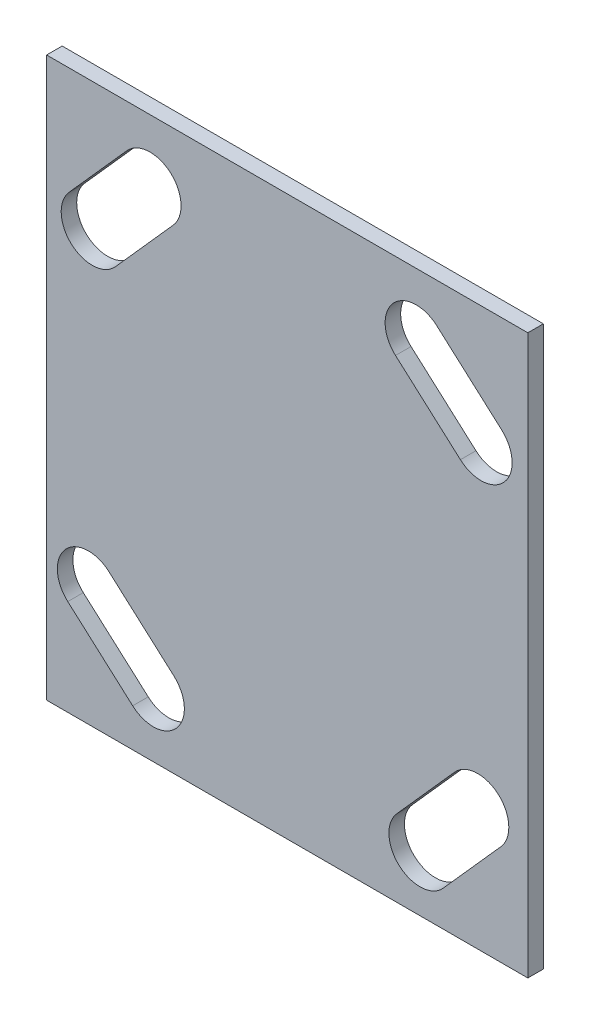
SolidWorks part; units mm, degrees
ref_plane "Front Plane" through (0, 0, 0) normal (0, 0, 1) x (1, 0, 0)
ref_plane "Top Plane" through (0, 0, 0) normal (0, 1, 0) x (1, 0, 0)
ref_plane "Right Plane" through (0, 0, 0) normal (1, 0, 0) x (0, 0, -1)
sketch "Flat Plate" plane through (0, 0, 0) normal (0, 0, 1) x (1, 0, 0)
  line L1 (-101.3811, 38.1949) -> (-2.9561, 38.1949)
  line L2 (-101.3811, 38.1949) -> (-101.3811, -76.1051)
  line L3 (-101.3811, -76.1051) -> (-2.9561, -76.1051)
  line L4 (-2.9561, 38.1949) -> (-2.9561, -76.1051)
  point P4 (-234.7829, 69.0702)
  dimension "D1" = 98.425
  dimension "D2" = 114.3
extrude "Castor Plate" add sketch "Flat Plate" along normal blind 3.175
sketch "Holes" plane through (0, 0, 3.175) normal (0, 0, 1) x (1, 0, 0)
  line L0 (-92.0593, 11.9365) -> (-80.2353, 25.2151) construction
  line L1 (-96.8016, 16.1593) -> (-84.9776, 29.4379)
  line L2 (-87.3169, 7.7136) -> (-75.4929, 20.9922)
  line L3 (-25.0198, -64.6333) -> (-13.1958, -51.3547) construction
  line L4 (-29.7621, -60.4105) -> (-17.9381, -47.1319)
  line L5 (-20.2774, -68.8562) -> (-8.4534, -55.5776)
  line L6 (-92.8385, -51.7333) -> (-79.5599, -63.5573) construction
  line L7 (-88.6157, -46.9909) -> (-75.3371, -58.8149)
  line L8 (-97.0614, -56.4756) -> (-83.7828, -68.2996)
  line L9 (-25.799, 25.3843) -> (-12.5204, 13.5603) construction
  line L10 (-21.5762, 30.1266) -> (-8.2976, 18.3026)
  line L11 (-30.0219, 20.6419) -> (-16.7433, 8.8179)
  arc A0 (-96.8016, 16.1593) -> (-87.3169, 7.7136) centre (-92.0593, 11.9365) ccw
  arc A1 (-75.4929, 20.9922) -> (-84.9776, 29.4379) centre (-80.2353, 25.2151) ccw
  arc A2 (-29.7621, -60.4105) -> (-20.2774, -68.8562) centre (-25.0198, -64.6333) ccw
  arc A3 (-8.4534, -55.5776) -> (-17.9381, -47.1319) centre (-13.1958, -51.3547) ccw
  arc A4 (-88.6157, -46.9909) -> (-97.0614, -56.4756) centre (-92.8385, -51.7333) ccw
  arc A5 (-83.7828, -68.2996) -> (-75.3371, -58.8149) centre (-79.5599, -63.5573) ccw
  arc A6 (-21.5762, 30.1266) -> (-30.0219, 20.6419) centre (-25.799, 25.3843) ccw
  arc A7 (-16.7433, 8.8179) -> (-8.2976, 18.3026) centre (-12.5204, 13.5603) ccw
  point P2 (-86.1473, 18.5758)
  point P9 (-19.1078, -57.994)
  point P16 (-86.1992, -57.6453)
  point P23 (-19.1597, 19.4723)
  point P28 (0, 0)
  point P29 (0, 0)
  point P30 (0, 0)
extrude "Cut-Extrude1" cut sketch "Holes" against normal blind 3.175
